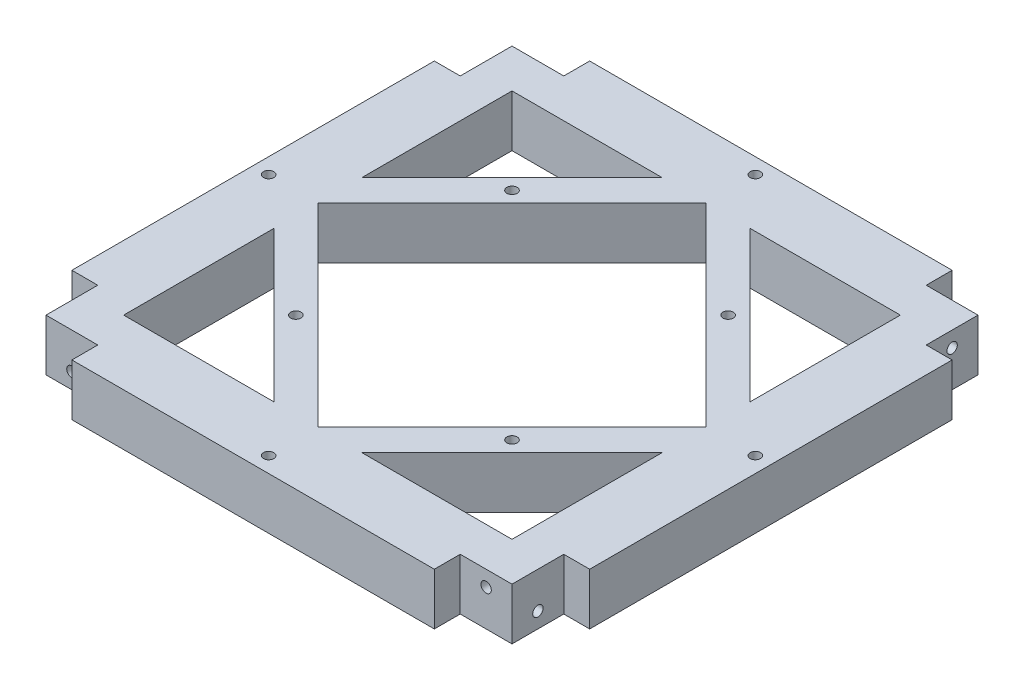
SolidWorks part; units mm, degrees
ref_plane "Front Plane" through (0, 0, 0) normal (0, 0, 1) x (1, 0, 0)
ref_plane "Top Plane" through (0, 0, 0) normal (0, 1, 0) x (1, 0, 0)
ref_plane "Right Plane" through (0, 0, 0) normal (1, 0, 0) x (0, 0, -1)
sketch "Sketch1" plane through (0, 0, 0) normal (0, 1, 0) x (1, 0, 0)
  line L1 (-50, 50) -> (50, 50)
  line L2 (-50, 50) -> (-50, -50)
  line L3 (-50, -50) -> (50, -50)
  line L4 (50, 50) -> (50, -50)
  line L5 (-50, 50) -> (50, -50) construction
  line L6 (-50, -50) -> (50, 50) construction
  point P0 (0, 0)
  dimension "D1" = 100
  dimension "D2" = 100
extrude "Boss-Extrude1" add sketch "Sketch1" along normal blind 10
sketch "Sketch2" plane through (0, 10, 0) normal (0, 1, 0) x (1, 0, 0)
  line L0 (0, 62.3904) -> (0, -71.6598) construction
  line L1 (72.3728, 0) -> (-85.564, 0) construction
  line L2 (35, 50) -> (35, 45)
  line L3 (50, 50) -> (-50, 50) construction
  line L4 (50, -50) -> (50, 50) construction
  line L5 (35, 45) -> (45, 45)
  line L6 (45, 45) -> (45, 35)
  line L7 (45, 35) -> (50, 35)
  line L8 (-45, 35) -> (-50, 35)
  line L9 (-45, 45) -> (-45, 35)
  line L10 (-35, 45) -> (-45, 45)
  line L11 (-35, 50) -> (-35, 45)
  line L12 (-45, -35) -> (-50, -35)
  line L13 (-45, -45) -> (-45, -35)
  line L14 (-35, -50) -> (-35, -45)
  line L15 (-35, -45) -> (-45, -45)
  line L16 (35, -50) -> (35, -45)
  line L17 (45, -35) -> (50, -35)
  line L18 (45, -45) -> (45, -35)
  line L19 (35, -45) -> (45, -45)
  line L20 (-50, 35) -> (-50, 50)
  line L21 (-50, 50) -> (-35, 50)
  line L22 (35, 50) -> (50, 50)
  line L23 (50, 50) -> (50, 35)
  line L24 (50, -35) -> (50, -50)
  line L25 (50, -50) -> (35, -50)
  line L26 (-35, -50) -> (-50, -50)
  line L27 (-50, -50) -> (-50, -35)
  dimension "D1" = 15
  dimension "D2" = 5
  dimension "D3" = 10
  dimension "D4" = 10
extrude "Cut-Extrude1" cut sketch "Sketch2" against normal through all
sketch "Sketch3" plane through (0, 10, 0) normal (0, 1, 0) x (1, 0, 0)
  line L1 (-37.5, 37.5) -> (37.5, 37.5)
  line L2 (-37.5, 37.5) -> (-37.5, -37.5)
  line L3 (-37.5, -37.5) -> (37.5, -37.5)
  line L4 (37.5, 37.5) -> (37.5, -37.5)
  line L5 (-37.5, 37.5) -> (37.5, -37.5) construction
  line L6 (-37.5, -37.5) -> (37.5, 37.5) construction
  point P0 (0, 0)
  dimension "D1" = 75
  dimension "D2" = 75
extrude "Cut-Extrude2" cut sketch "Sketch3" against normal blind 10
sketch "Sketch4" plane through (0, 10, 0) normal (0, 1, 0) x (1, 0, 0)
  line L0 (0, 37.5) -> (-37.5, 0)
  line L1 (37.5, 37.5) -> (-37.5, 37.5) construction
  line L2 (-37.5, 37.5) -> (-37.5, -37.5) construction
  line L3 (-37.5, 0) -> (0, -37.5)
  line L4 (-37.5, -37.5) -> (37.5, -37.5) construction
  line L5 (0, -37.5) -> (37.5, 0)
  line L6 (37.5, -37.5) -> (37.5, 37.5) construction
  line L7 (37.5, 0) -> (0, 37.5)
  line L8 (45.9853, 0) -> (0, 45.9853)
  line L9 (0, 45.9853) -> (-45.9853, 0)
  line L10 (-45.9853, 0) -> (0, -45.9853)
  line L11 (0, -45.9853) -> (45.9853, 0)
  dimension "D1" = 6
extrude "Boss-Extrude2" add sketch "Sketch4" against normal blind 10
sketch "Sketch9" plane through (-45, 0, 0) normal (-1, 0, 0) x (0, 0, 1)
  line L0 (-40, 0) -> (-40, 3) construction
  line L1 (-35, 0) -> (-45, 0) construction
  line L2 (0, 17.1785) -> (0, -16.8105) construction
  circle A0 centre (-40, 3) radius 1
  dimension "D2" = 2
  dimension "D1" = 3
sketch "Sketch10" plane through (0, 10, 0) normal (0, 1, 0) x (1, 0, 0)
  line L0 (-56.4507, 0) -> (100.8663, 0) construction
  line L1 (0, 53.1554) -> (0, -62.5829) construction
  line L2 (35, 50) -> (-35, 50) construction
  circle A0 centre (0, 47) radius 1
  circle A1 centre (0, -47) radius 1
  dimension "D1" = 2
  dimension "D2" = 3
extrude "Cut-Extrude7" cut sketch "Sketch10" against normal through all
sketch "Sketch11" plane through (0, 10, 0) normal (0, 1, 0) x (1, 0, 0)
  line L0 (0, 59.1443) -> (0, -66.5374) construction
  line L1 (-50, 35) -> (-50, -35) construction
  circle A0 centre (-47, 0) radius 1
  circle A1 centre (47, 0) radius 1
  dimension "D1" = 2
  dimension "D2" = 3
extrude "Cut-Extrude8" cut sketch "Sketch11" against normal through all
sketch "Sketch12" plane through (0, 10, 0) normal (0, 1, 0) x (1, 0, 0)
  line L0 (0, 0) -> (-31.1625, 31.1625) construction
  line L1 (0, 62.2391) -> (0, -70.1479) construction
  line L2 (-72.2111, 0) -> (122.2431, 0) construction
  line L3 (-8.4853, 37.5) -> (-37.5, 8.4853) construction
  line L4 (-34.8249, 11.1604) -> (-30.5823, 6.9177) construction
  line L5 (0, 37.5) -> (-37.5, 0) construction
  line L6 (-30.5823, 6.9177) -> (-32.7036, 9.039) construction
  line L7 (-32.7036, 9.039) -> (-20.8713, 20.8713) construction
  circle A0 centre (-20.8713, 20.8713) radius 1
  circle A1 centre (20.8713, 20.8713) radius 1
  circle A2 centre (20.8713, -20.8713) radius 1
  circle A3 centre (-20.8713, -20.8713) radius 1
  dimension "D1" = 2
extrude "Cut-Extrude9" cut sketch "Sketch12" against normal through all
sketch "Sketch13" plane through (0, 0, -45) normal (0, 0, -1) x (-1, 0, 0)
  line L0 (0, 22.954) -> (0, -4.7217) construction
  line L1 (40, 10) -> (40, 7) construction
  line L2 (45, 10) -> (35, 10) construction
  circle A0 centre (40, 7) radius 1
  dimension "D2" = 2
  dimension "D1" = 3
extrude "Cut-Extrude11" cut sketch "Sketch9" against normal blind 10
extrude "Cut-Extrude12" cut sketch "Sketch13" against normal blind 10
sketch "Sketch14" plane through (-45, 0, 0) normal (-1, 0, 0) x (0, 0, 1)
  line L0 (45, 10) -> (35, 10) construction
  circle A0 centre (40, 7) radius 1
  point P4 (40, 10)
  dimension "D1" = 2
  dimension "D2" = 3
extrude "Cut-Extrude13" cut sketch "Sketch14" against normal blind 10
sketch "Sketch15" plane through (0, 0, 45) normal (0, 0, 1) x (1, 0, 0)
  line L0 (-35, 0) -> (-45, 0) construction
  circle A0 centre (-40, 3) radius 1
  dimension "D1" = 2
  dimension "D2" = 3
extrude "Cut-Extrude14" cut sketch "Sketch15" against normal blind 10
sketch "Sketch16" plane through (0, 0, 45) normal (0, 0, 1) x (1, 0, 0)
  line L0 (45, 10) -> (35, 10) construction
  circle A0 centre (40, 7) radius 1
  dimension "D1" = 2
  dimension "D2" = 3
extrude "Cut-Extrude15" cut sketch "Sketch16" against normal blind 10
sketch "Sketch17" plane through (45, 0, 0) normal (1, 0, 0) x (0, 0, -1)
  line L0 (-35, 0) -> (-45, 0) construction
  circle A0 centre (-40, 3) radius 1
  dimension "D1" = 2
  dimension "D2" = 3
extrude "Cut-Extrude16" cut sketch "Sketch17" against normal blind 10
sketch "Sketch18" plane through (45, 0, 0) normal (1, 0, 0) x (0, 0, -1)
  line L0 (45, 10) -> (35, 10) construction
  circle A0 centre (40, 7) radius 1
  dimension "D1" = 2
  dimension "D2" = 3
extrude "Cut-Extrude17" cut sketch "Sketch18" against normal blind 10
sketch "Sketch19" plane through (0, 0, -45) normal (0, 0, -1) x (-1, 0, 0)
  line L0 (-35, 10) -> (-45, 10) construction
  circle A0 centre (-40, 3) radius 1
  dimension "D1" = 2
  dimension "D2" = 7
extrude "Cut-Extrude18" cut sketch "Sketch19" against normal blind 10
